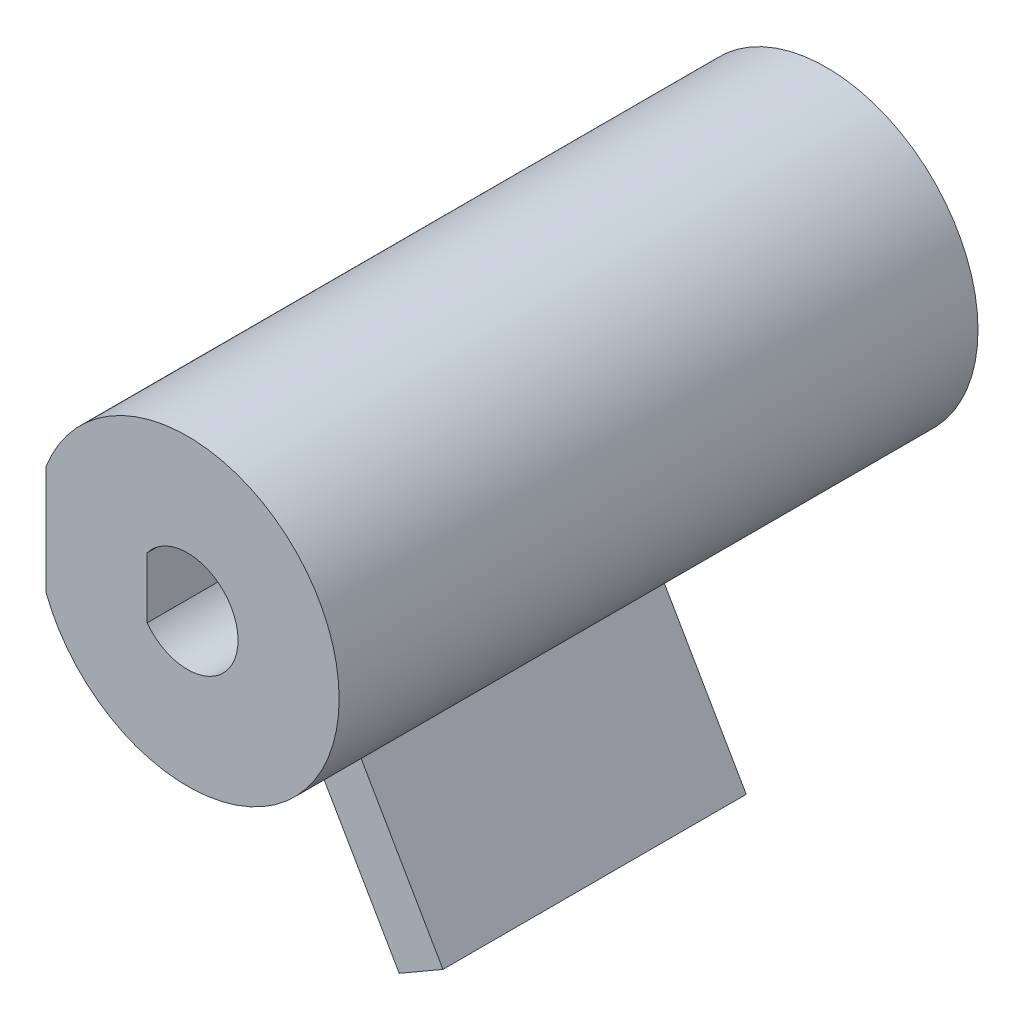
SolidWorks part; units mm, degrees
material "1.4000 (X6Cr13)"
ref_plane "前视基准面" through (0, 0, 0) normal (0, 0, 1) x (1, 0, 0)
ref_plane "上视基准面" through (0, 0, 0) normal (0, 1, 0) x (1, 0, 0)
ref_plane "右视基准面" through (0, 0, 0) normal (1, 0, 0) x (0, 0, -1)
other "Configuration Table"
sketch "草图1" plane through (0, 0, 0) normal (0, 0, 1) x (1, 0, 0)
  line L0 (-4, 3) -> (-4, -3)
  arc A0 (-4, -3) -> (-4, 3) centre (0, 0) ccw
  dimension "D2" = 5
  dimension "D1" = 6
extrude "拉伸-薄壁1" add sketch "草图1" along normal blind 63.2 thin
sketch "草图9" plane through (0, 0, 63.2) normal (0, 0, 1) x (1, 0, 0)
  line L0 (-14, -5.3852) -> (-14, 5.3852)
  line L4 (-14, -5.3852) -> (4.3416, -37.1538)
  dimension "D1" = 150
extrude "拉伸-薄壁4" add sketch "草图9" along normal mid plane 30 from offset 31.6 thin offset against normal yes
